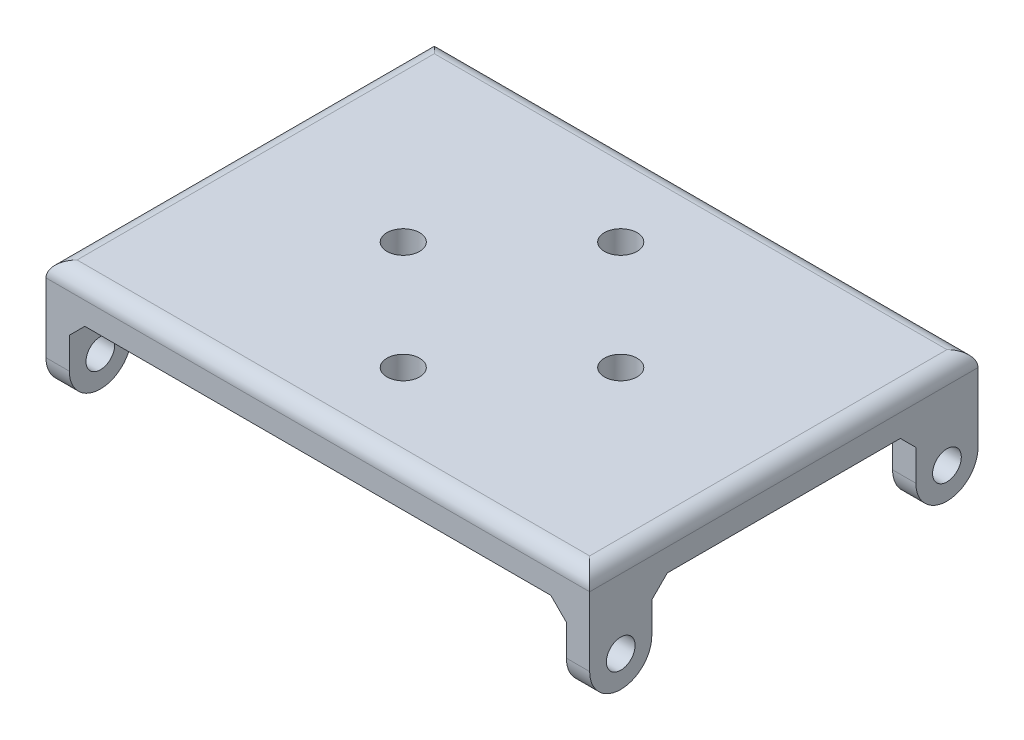
SolidWorks part; units mm, degrees
ref_plane "前视基准面" through (0, 0, 0) normal (0, 0, 1) x (1, 0, 0)
ref_plane "上视基准面" through (0, 0, 0) normal (0, 1, 0) x (1, 0, 0)
ref_plane "右视基准面" through (0, 0, 0) normal (1, 0, 0) x (0, 0, -1)
other "Configuration Table"
sketch "草图1" plane through (0, 0, 0) normal (0, 1, 0) x (1, 0, 0)
  line L1 (-17.5, -12.5) -> (17.5, -12.5)
  line L2 (-17.5, -12.5) -> (-17.5, 12.5)
  line L3 (-17.5, 12.5) -> (17.5, 12.5)
  line L4 (17.5, -12.5) -> (17.5, 12.5)
  line L5 (-17.5, -12.5) -> (17.5, 12.5) construction
  line L6 (-17.5, 12.5) -> (17.5, -12.5) construction
  point P0 (0, 0)
  dimension "D1" = 35
  dimension "D2" = 25
extrude "凸台-拉伸1" add sketch "草图1" along normal mid plane 2.45
sketch "草图2" plane through (-17.5, 0, 0) normal (-1, 0, 0) x (0, 0, 1)
  line L0 (-12.5, -1.225) -> (-12.5, -4.225)
  line L1 (-8.5, -4.225) -> (-8.5, -1.225)
  line L2 (-12.5, -1.225) -> (12.5, -1.225) construction
  line L3 (0, 0) -> (0, -16.0156) construction
  line L4 (-8.5, -1.225) -> (-12.5, -1.225)
  line L5 (8.5, -1.225) -> (12.5, -1.225)
  line L6 (8.5, -4.225) -> (8.5, -1.225)
  line L7 (12.5, -1.225) -> (12.5, -4.225)
  arc A0 (-12.5, -4.225) -> (-8.5, -4.225) centre (-10.5, -4.225) ccw
  arc A1 (12.5, -4.225) -> (8.5, -4.225) centre (10.5, -4.225) cw
  dimension "D1" = 21
  dimension "D2" = 3
extrude "凸台-拉伸2" add sketch "草图2" against normal blind 1.5
sketch "草图4" plane through (-17.5, 0, 0) normal (-1, 0, 0) x (0, 0, 1)
  line L0 (0, 0) -> (0, -8.9551) construction
  circle A0 centre (-10.5, -4.225) radius 0.925
  circle A1 centre (10.5, -4.225) radius 0.925
  dimension "D1" = 1.85
extrude "切除-拉伸1" cut sketch "草图4" against normal through all
mirror "镜向1" about plane through (0, 0, 0) normal (1, 0, 0) of "凸台-拉伸2", "切除-拉伸1"
chamfer "倒角1" distance 1 angle 45 8 edges at (16, -1.225, -10.5) (16.75, -1.225, -8.5) (16, -1.225, 10.5) (16.75, -1.225, 8.5) (-16, -1.225, 10.5) (-16.75, -1.225, 8.5) (-16, -1.225, -10.5) (-16.75, -1.225, -8.5)
fillet "圆角1" radius 1 4 edges at (-17.5, 1.225, 0) (0, 1.225, -12.5) (17.5, 1.225, 0) (0, 1.225, 12.5)
sketch "草图5" plane through (0, 1.225, 0) normal (0, 1, 0) x (1, 0, 0)
  circle A0 centre (0, 0) radius 7 construction
  circle A1 centre (0, 7) radius 1.05
  circle A2 centre (7, 0) radius 1.05
  circle A3 centre (-7, 0) radius 1.05
  circle A4 centre (0, -7) radius 1.05
  dimension "D1" = 14
  dimension "D2" = 2.1
extrude "切除-拉伸2" cut sketch "草图5" against normal through all
